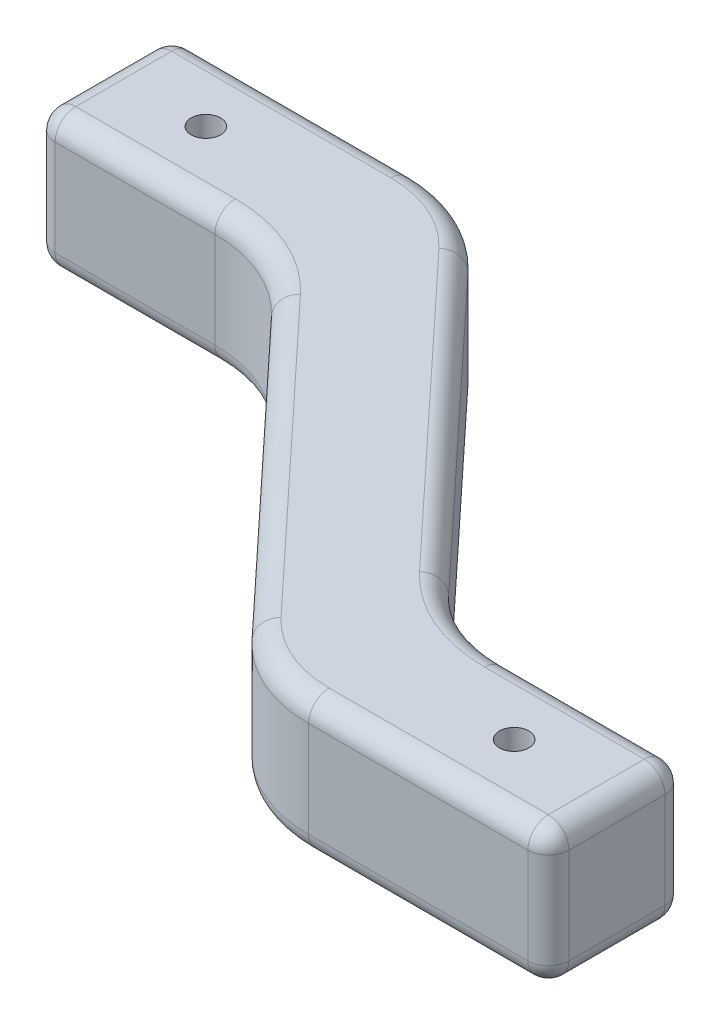
SolidWorks part; units mm, degrees
ref_plane "Alzado" through (0, 0, 0) normal (0, 0, 1) x (1, 0, 0)
ref_plane "Planta" through (0, 0, 0) normal (0, 1, 0) x (1, 0, 0)
ref_plane "Vista lateral" through (0, 0, 0) normal (1, 0, 0) x (0, 0, -1)
sketch "Croquis1" plane through (0, 0, 0) normal (0, 1, 0) x (1, 0, 0)
  line L0 (-65, 0) -> (65, 0) construction
  line L1 (-65, 0) -> (-21.3058, 0)
  line L2 (-21.3058, 0) -> (30, -55)
  line L3 (30, -55) -> (65, -55)
  line L4 (65, -55) -> (65, -75)
  line L5 (65, -75) -> (21.3058, -75)
  line L6 (21.3058, -75) -> (-30, -20)
  line L7 (-30, -20) -> (-65, -20)
  line L8 (-65, -20) -> (-65, 0)
  line L9 (-65, -10) -> (-50, -10) construction
  line L10 (50, -65) -> (65, -65) construction
  circle A0 centre (-50, -10) radius 2.15
  circle A1 centre (50, -65) radius 2.15
  point P0 (-65, -10)
  point P4 (0, 0)
  point P13 (65, -65)
  dimension "D8" = 4.3
  dimension "D1" = 130
  dimension "D2" = 20
  dimension "D3" = 35
  dimension "D4" = 55
  dimension "D5" = 20
  dimension "D6" = 15
  dimension "D7" = 15
extrude "Saliente-Extruir1" add sketch "Croquis1" along normal blind 20
fillet "Redondeo1" radius 20 4 edges at (21.3058, 10, 75) (30, 10, 55) (-21.3058, 10, 0) (-30, 10, 20)
sketch "Croquis3" plane through (0, 20, 0) normal (0, 1, 0) x (1, 0, 0)
  line L5 (65, -52.5479) -> (45, -52.5479)
  line L6 (45, -52.5479) -> (45, -75)
  line L7 (45, -75) -> (65, -75)
  line L8 (65, -75) -> (65, -52.5479)
  line L9 (30, -75) -> (65, -75) construction
  dimension "D2" = 20
extrude "Cortar-Extruir2" [suppressed] cut sketch "Croquis3" against normal blind 10
sketch "Croquis5" plane through (0, 0, 0) normal (0, -1, 0) x (1, 0, 0)
  line L0 (-65, 0) -> (-45, 0)
  line L1 (-45, 0) -> (-45, 24.0911)
  line L2 (-45, 24.0911) -> (-65, 24.0911)
  line L3 (-65, 24.0911) -> (-65, 0)
  dimension "D1" = 20
extrude "Cortar-Extruir3" [suppressed] cut sketch "Croquis5" against normal blind 10
fillet "Redondeo2" radius 3 28 edges at (-4.3471, 0, 47.5) (-30.7208, 0, 21.6581) (4.3471, 0, 27.5) (22.0266, 0, 73.3419) (-4.3471, 20, 47.5) (-30.7208, 20, 21.6581) (-51.8471, 0, 20) (-22.0266, 0, 1.6581) (30.7208, 0, 53.3419) (47.5, 0, 75) (22.0266, 20, 73.3419) (-65, 10, 20) (-51.8471, 20, 20) (-65, 0, 10) (-47.5, 0, 0) (51.8471, 0, 55) (65, 0, 65) (65, 10, 75) (47.5, 20, 75) (-65, 20, 10) (-65, 10, 0) (65, 10, 55) (65, 20, 65) (-47.5, 20, 0) (51.8471, 20, 55) (-22.0266, 20, 1.6581) (30.7208, 20, 53.3419) (4.3471, 20, 27.5)
